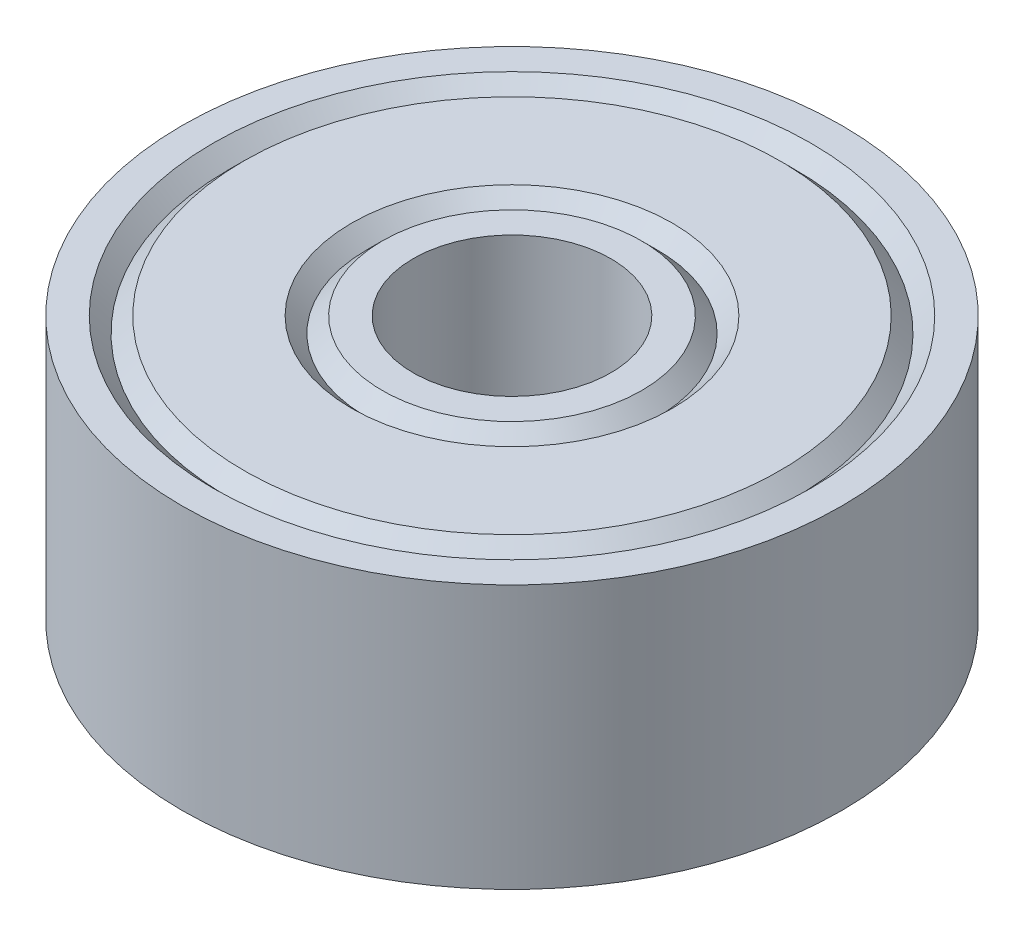
SolidWorks part; units mm, degrees
ref_plane "Front Plane" through (0, 0, 0) normal (0, 0, 1) x (1, 0, 0)
ref_plane "Top Plane" through (0, 0, 0) normal (0, 1, 0) x (1, 0, 0)
ref_plane "Right Plane" through (0, 0, 0) normal (1, 0, 0) x (0, 0, -1)
sketch "Sketch1" plane through (0, 0, 0) normal (0, 0, 1) x (1, 0, 0)
  line L0 (0, 2) -> (0, -2) construction
  line L1 (-1.5, 2) -> (-1.9667, 2)
  line L2 (-1.5, 2) -> (-1.5, -2)
  line L3 (-1.5, -2) -> (-1.9667, -2)
  line L4 (-5, 2) -> (-5, -2)
  line L5 (-4.5333, 2) -> (-4.3, 1.7667)
  line L6 (-4.3, 1.7667) -> (-4.0667, 2)
  line L7 (-2.4333, 2) -> (-2.2, 1.7667)
  line L8 (-2.2, 1.7667) -> (-1.9667, 2)
  line L9 (-4.5333, -2) -> (-4.3, -1.7667)
  line L10 (-4.3, -1.7667) -> (-4.0667, -2)
  line L11 (-2.4333, -2) -> (-2.2, -1.7667)
  line L12 (-2.2, -1.7667) -> (-1.9667, -2)
  line L13 (-2.4333, -2) -> (-4.0667, -2)
  line L14 (-4.5333, -2) -> (-5, -2)
  line L15 (-4.5333, 2) -> (-5, 2)
  line L16 (-2.4333, 2) -> (-4.0667, 2)
  line L17 (-4.3, 1.7667) -> (-2.2, 1.7667) construction
  line L18 (-4.3, 1.7667) -> (-4.3, -1.7667) construction
  line L19 (-2.2, -1.7667) -> (-4.3, -1.7667) construction
  line L20 (-2.2, 1.7667) -> (-2.2, -1.7667) construction
  line L21 (-4.3, 0) -> (-3.6, 0) construction
  line L22 (-1.9667, 2) -> (-2.4333, 2) construction
  line L23 (-3.6, 0) -> (-2.9, 0) construction
  line L24 (-4.3, 0) -> (-5, 0) construction
  line L25 (-2.9, 0) -> (-2.2, 0) construction
  line L26 (-2.2, 0) -> (-1.5, 0) construction
  dimension "D1" = 4
  dimension "D2" = 3
  dimension "D3" = 10
revolve "Revolve1" add sketch "Sketch1" angle 360 about L0
